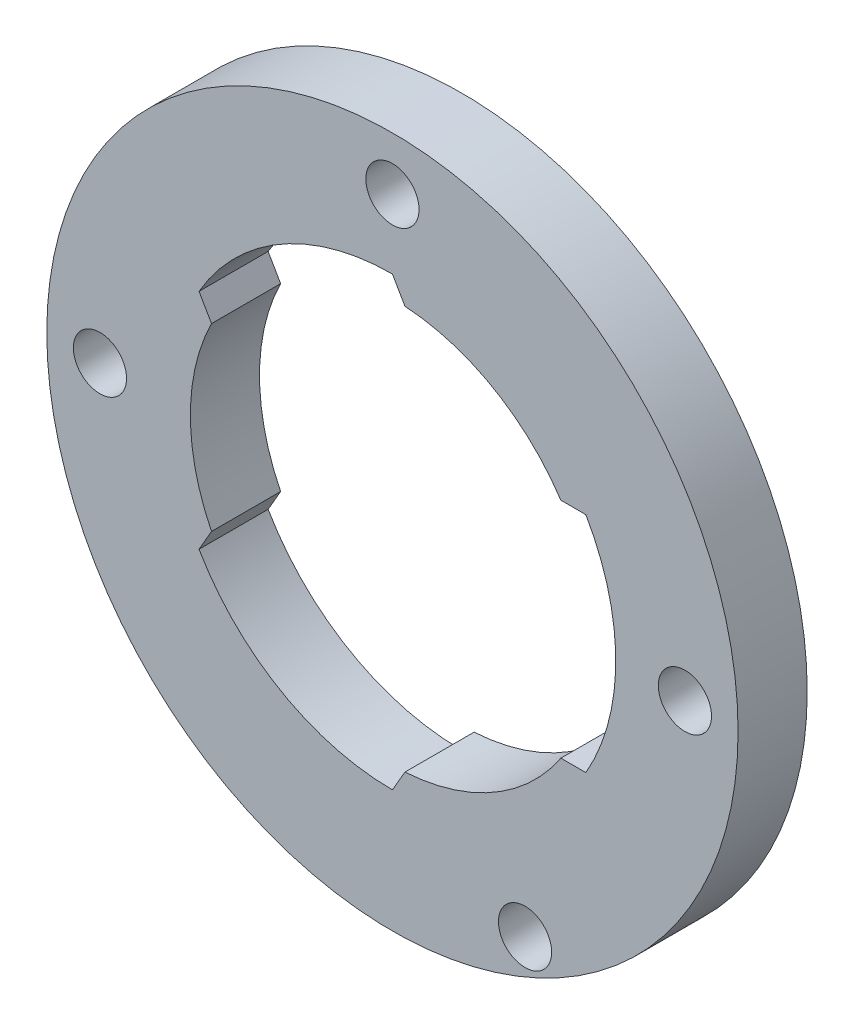
SolidWorks part; units mm, degrees
ref_plane "Front Plane" through (0, 0, 0) normal (0, 0, 1) x (1, 0, 0)
ref_plane "Top Plane" through (0, 0, 0) normal (0, 1, 0) x (1, 0, 0)
ref_plane "Right Plane" through (0, 0, 0) normal (1, 0, 0) x (0, 0, -1)
sketch "Sketch1" plane through (0, 0, 0) normal (0, 0, 1) x (1, 0, 0)
  line L1 (41.275, -41.275) -> (-41.275, -41.275) construction
  line L2 (41.275, -41.275) -> (41.275, 41.275) construction
  line L3 (41.275, 41.275) -> (-41.275, 41.275) construction
  line L4 (-41.275, -41.275) -> (-41.275, 41.275) construction
  line L5 (41.275, -41.275) -> (-41.275, 41.275) construction
  line L6 (41.275, 41.275) -> (-41.275, -41.275) construction
  circle A0 centre (0, 0) radius 24.13
  circle A1 centre (0, 0) radius 41.275
  dimension "D1" = 48.26
  dimension "D2" = 82.55
extrude "Boss-Extrude1" add sketch "Sketch1" along normal mid plane 8.255
hole_wizard "Ø3.4 (3.4) Diameter Hole1" positions "Sketch2" profile "Sketch3" hole size "Ø3.4" standard "ANSI Metric" end condition through all
sketch "Sketch2" plane through (0, 0, 4.1275) normal (0, 0, 1) x (1, 0, 0)
  line L1 (0, -34.925) -> (-34.925, 0)
  line L2 (0, -34.925) -> (34.925, 0)
  line L3 (34.925, 0) -> (0, 34.925)
  line L4 (-34.925, 0) -> (0, 34.925)
  line L5 (0, -34.925) -> (0, 34.925) construction
  line L6 (34.925, 0) -> (-34.925, 0) construction
  line L8 (4.5403, 0) -> (-4.5403, 0) construction
  circle A0 centre (0, 0) radius 34.925 construction
  point P5 (0, 34.925)
  point P7 (34.925, 0)
  point P11 (-34.925, 0)
  dimension "D1" = 69.85
  dimension "D2" = 90
sketch "Sketch3" plane through (-34.925, 0, 4.1275) normal (1, 0, 0) x (0, -1, 0)
  line L0 (0, 0) -> (0, 8.255)
  line L1 (0, 8.255) -> (1.7, 8.255)
  line L2 (1.7, 8.255) -> (1.7, 0)
  line L5 (1.7, 0) -> (0, 0)
  line L11 (0, -6.35) -> (0, 107.95) construction
  dimension "Thru Hole Dia." = 3.4
  dimension "Thru Hole Depth" = 8.255
sketch "Sketch5" plane through (0, 0, -4.1275) normal (0, 0, -1) x (-1, 0, 0)
  line L0 (0, 0) -> (-23.0969, -13.335) construction
  line L1 (0, 0) -> (-23.0969, 13.335) construction
  line L3 (0, 0) -> (-26.67, 0) construction
  line L4 (-23.0969, 13.335) -> (0, 13.335)
  line L5 (0, 4.5403) -> (0, -4.5403) construction
  line L6 (0, 13.335) -> (0, -13.335)
  line L7 (0, -13.335) -> (-23.0969, -13.335)
  arc A0 (-23.0969, 13.335) -> (-23.0969, -13.335) centre (0, 0) ccw
  dimension "D1" = 53.34
  dimension "D3" = 60
extrude "Cut-Extrude2" cut sketch "Sketch5" against normal through all
pattern_circular "CirPattern1" count 3 over 360 about axis through (0, 0, 0) along (0, 0, 1) of "Cut-Extrude2"
hole_wizard "Ø3.4 (3.4) Diameter Hole2" positions "Sketch6" profile "Sketch7" hole size "Ø3.4" standard "ANSI Metric" end condition through all
sketch "Sketch6" plane through (0, 0, 4.1275) normal (0, 0, 1) x (1, 0, 0)
  line L0 (0, 0) -> (15.8334, -33.9548) construction
  line L2 (0, -4.5403) -> (0, 4.5403) construction
  circle A0 centre (0, 0) radius 37.465 construction
  point P0 (15.8334, -33.9548)
  dimension "D1" = 74.93
  dimension "D2" = 25
sketch "Sketch7" plane through (15.8334, -33.9548, 4.1275) normal (1, 0, 0) x (0, -1, 0)
  line L0 (0, 0) -> (0, 8.255)
  line L1 (0, 8.255) -> (1.7, 8.255)
  line L2 (1.7, 8.255) -> (1.7, 0)
  line L5 (1.7, 0) -> (0, 0)
  line L11 (0, -6.35) -> (0, 107.95) construction
  dimension "Thru Hole Dia." = 3.4
  dimension "Thru Hole Depth" = 8.255
sketch "Sketch8" plane through (0, 0, 4.1275) normal (0, 0, 1) x (1, 0, 0)
  circle A0 centre (0, 34.925) radius 3.175
  circle A1 centre (34.925, 0) radius 3.175
  circle A2 centre (15.8334, -33.9548) radius 3.175
  circle A3 centre (-34.925, 0) radius 3.175
  dimension "D1" = 6.35
extrude "Cut-Extrude3" cut sketch "Sketch8" against normal blind 6
